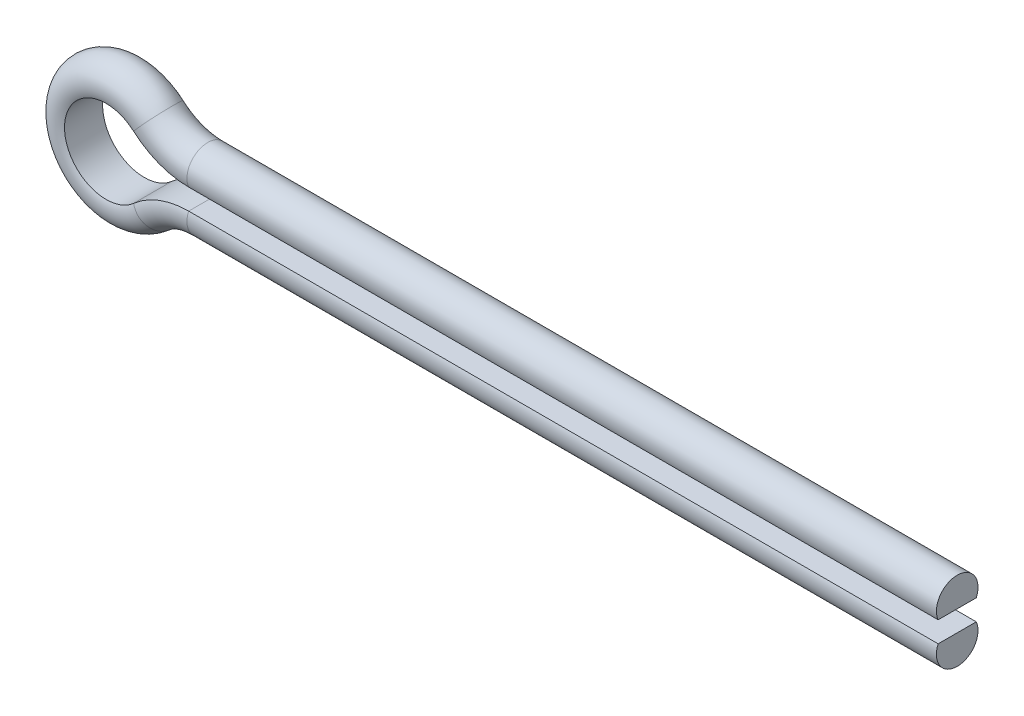
SolidWorks part; units mm, degrees
ref_plane "Front Plane" through (0, 0, 0) normal (0, 0, 1) x (1, 0, 0)
ref_plane "Top Plane" through (0, 0, 0) normal (0, 1, 0) x (1, 0, 0)
ref_plane "Right Plane" through (0, 0, 0) normal (1, 0, 0) x (0, 0, -1)
sketch "Sketch1" plane through (0, 0, 0) normal (0, 0, 1) x (1, 0, 0)
  line L0 (9.9216, 1.25) -> (100, 1.25)
  line L3 (100, 1.25) -> (9.9216, 1.25)
  line L4 (9.9216, -1.25) -> (100, -1.25)
  line L5 (100, -1.25) -> (9.9216, -1.25)
  arc A3 (3.3072, 3.75) -> (3.3072, -3.75) centre (0, 0) ccw
  arc A4 (3.3072, 3.75) -> (9.9216, 1.25) centre (9.9216, 11.25) ccw
  arc A5 (3.3072, -3.75) -> (9.9216, -1.25) centre (9.9216, -11.25) cw
  point P9 (10.8312, 10.3772)
  point P11 (0, 0)
  point P12 (0, 0)
  point P13 (0, 0)
  point P14 (0, 0)
  point P15 (0, 0)
  dimension "D1" = 10
  dimension "D2" = 5
  dimension "D4" = 100
  dimension "D3" = 2.5
ref_plane "Plane1" through (100, 0, 0) normal (1, 0, 0) x (0, 0, -1)
sketch "Sketch2" plane through (100, 0, 0) normal (1, 0, 0) x (0, 0, -1)
  line L0 (-2.2913, -1.25) -> (2.2913, -1.25)
  arc A0 (-2.2913, -1.25) -> (2.2913, -1.25) centre (0, -2.25) ccw
  point P3 (0, -4.75)
  point P4 (0, -1.25)
  dimension "D1" = 2.5
  dimension "D2" = 3.5
sweep "Sweep1" add profiles "Sketch2" path "Sketch1"
